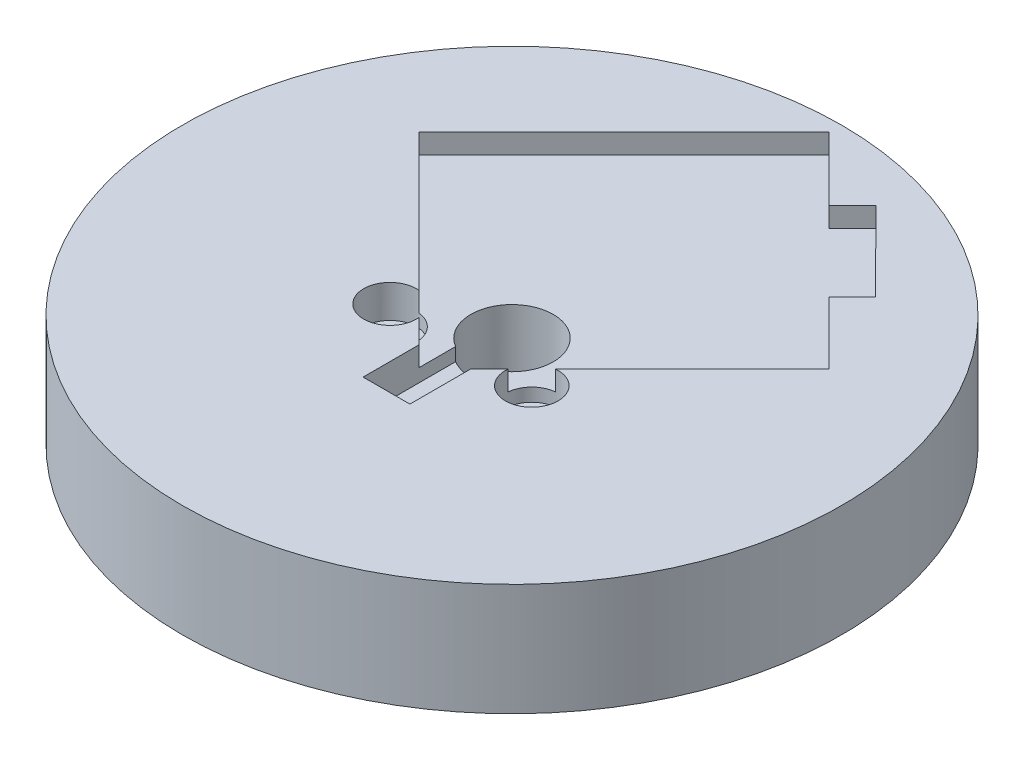
SolidWorks part; units mm, degrees
ref_plane "Front Plane" through (0, 0, 0) normal (0, 0, 1) x (1, 0, 0)
ref_plane "Top Plane" through (0, 0, 0) normal (0, 1, 0) x (1, 0, 0)
ref_plane "Right Plane" through (0, 0, 0) normal (1, 0, 0) x (0, 0, -1)
sketch "Sketch2" plane through (0, 0, 0) normal (0, 1, 0) x (1, 0, 0)
  circle A0 centre (0, 0) radius 50
extrude "Boss-Extrude1" add sketch "Sketch2" along normal blind 17 contours A0
sketch "Sketch4" plane through (0, 17, 0) normal (0, 1, 0) x (1, 0, 0)
  circle A0 centre (0, 0) radius 6.25
  dimension "D1" = 12.5
extrude "Cut-Extrude1" cut sketch "Sketch4" against normal blind 17 contours A0
sketch "Sketch6" plane through (0, 17, 0) normal (0, 1, 0) x (1, 0, 0)
  line L0 (-5.9779, 23.0428) -> (5.9779, 10.9572)
  line L1 (-5.9779, 23.0428) -> (13.2168, 42.0313)
  line L2 (5.9779, 10.9572) -> (25.1725, 29.9458)
  line L3 (13.2168, 42.0313) -> (25.1725, 29.9458)
  point P2 (15.5752, 20.4515)
  point P5 (3.6195, 32.537)
  dimension "D1" = 17
  dimension "D2" = 27
sketch "Sketch7" plane through (0, 17, 0) normal (0, 1, 0) x (1, 0, 0)
  circle A0 centre (-10.75, -7.75) radius 4
  dimension "D1" = 8
extrude "Cut-Extrude2" cut sketch "Sketch7" against normal blind 5 contours A0
mirror "Mirror1" about plane through (0, 0, 0) normal (1, 0, 0) of "Cut-Extrude2"
sketch "Sketch8" plane through (0, 17, 0) normal (0, 1, 0) x (1, 0, 0)
  line L1 (-3.1796, -5.3808) -> (3.9199, -5.3808)
  line L2 (-3.1796, -5.3808) -> (-3.1796, -19.4129)
  line L3 (-3.1796, -19.4129) -> (3.9199, -19.4129)
  line L4 (3.9199, -5.3808) -> (3.9199, -19.4129)
  circle A0 centre (0, 0) radius 6.25 construction
extrude "Cut-Extrude3" cut sketch "Sketch8" against normal blind 5
sketch "Sketch9" plane through (0, 17, 0) normal (0, 1, 0) x (1, 0, 0)
  line L0 (-31.1127, 17) -> (0, 48.1127)
  line L1 (-31.1127, 17) -> (0, -14.1127)
  line L2 (0, 48.1127) -> (31.1127, 17)
  line L3 (0, -14.1127) -> (31.1127, 17)
  point P0 (0, 0)
  dimension "D1" = 44
  dimension "D2" = 44
extrude "Cut-Extrude4" cut sketch "Sketch9" against normal blind 3
extrude "Cut-Extrude5" cut sketch "Sketch6" against normal blind 3
